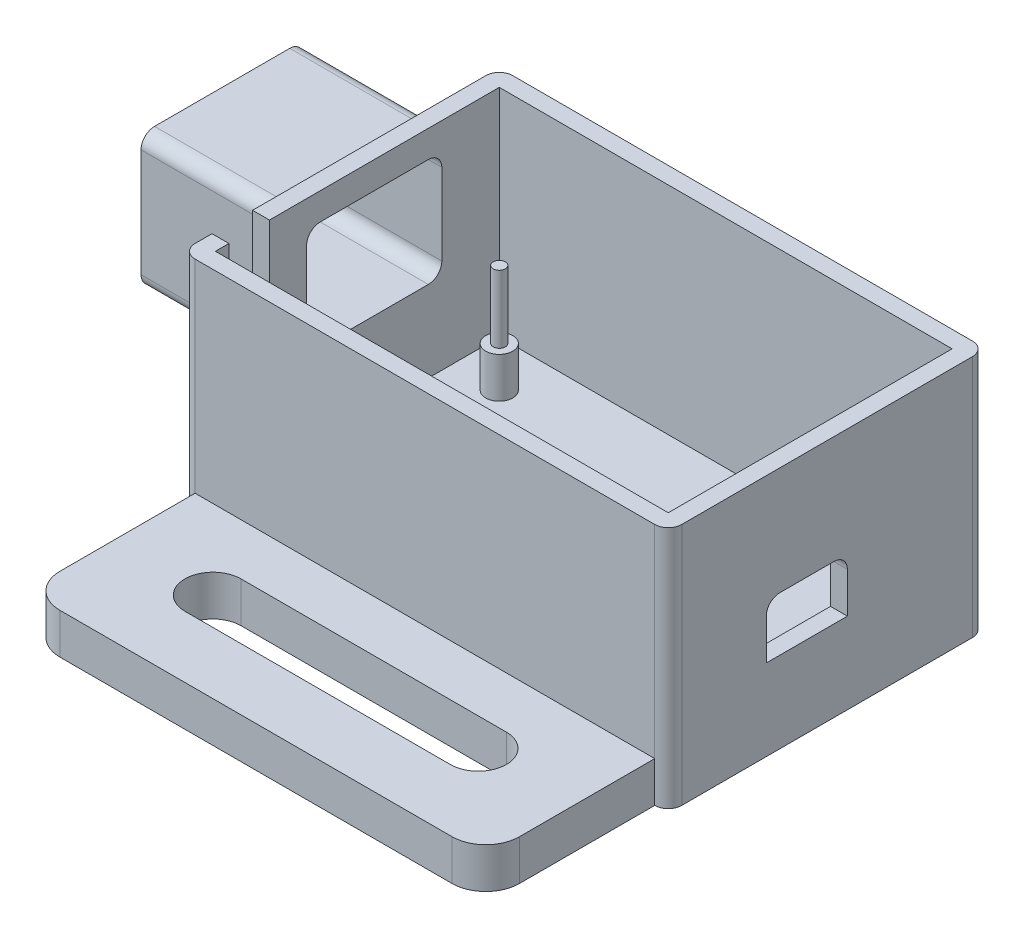
SolidWorks part; units mm, degrees
ref_plane "Front Plane" through (0, 0, 0) normal (0, 0, 1) x (1, 0, 0)
ref_plane "Top Plane" through (0, 0, 0) normal (0, 1, 0) x (1, 0, 0)
ref_plane "Right Plane" through (0, 0, 0) normal (1, 0, 0) x (0, 0, -1)
sketch "Sketch1" plane through (0, 0, 0) normal (0, 1, 0) x (1, 0, 0)
  line L0 (-10.5, -10.5) -> (-10.5, 36.5)
  line L1 (0, 0) -> (51, 0) construction
  line L2 (0, 0) -> (0, 26) construction
  line L3 (0, 26) -> (51, 26) construction
  line L4 (51, 0) -> (51, 26) construction
  line L5 (-10.5, 36.5) -> (61.5, 36.5)
  line L6 (61.5, -10.5) -> (61.5, 36.5)
  line L7 (-10.5, -10.5) -> (61.5, -10.5)
  line L8 (25.5, 36.5) -> (25.5, -10.5) construction
  line L9 (-10.5, 13) -> (61.5, 13) construction
  dimension "D1" = 51
  dimension "D2" = 26
  dimension "D3" = 10.5
extrude "Boss-Extrude1" add sketch "Sketch1" along normal blind 4
sketch "Sketch2" plane through (0, 4, 0) normal (0, 1, 0) x (1, 0, 0)
  line L0 (-3, 13) -> (54, 13) construction
  line L1 (25.5, 29) -> (25.5, -3) construction
  line L8 (-3, 29) -> (-3, -3)
  line L9 (54, 29) -> (-3, 29)
  line L10 (54, -3) -> (54, 29)
  line L11 (-3, -3) -> (54, -3)
  line L12 (-3, 29) -> (-3, -3) construction
  line L13 (54, 29) -> (-3, 29) construction
  line L14 (54, -3) -> (54, 29) construction
  line L15 (-3, -3) -> (54, -3) construction
  circle A4 centre (-1.2, 27.2) radius 0.9
  circle A5 centre (-1.2, -1.2) radius 0.9
  circle A6 centre (52.2, -1.2) radius 0.9
  circle A7 centre (52.2, 27.2) radius 0.9
  dimension "D2" = 1.8
  dimension "D3" = 1.8
  dimension "D4" = 1.8
  dimension "D1" = 7.5
sketch "Sketch3" plane through (0, 4, 0) normal (0, 1, 0) x (1, 0, 0)
  line L0 (61.5, -10.5) -> (61.5, 36.5) construction
  line L1 (-10.5, -10.5) -> (61.5, -10.5) construction
  line L2 (61.5, 36.5) -> (-10.5, 36.5) construction
  line L3 (-10.5, 36.5) -> (-10.5, -10.5) construction
  line L4 (61.5, -10.5) -> (61.5, 36.5)
  line L5 (-10.5, -10.5) -> (61.5, -10.5)
  line L6 (61.5, 36.5) -> (-10.5, 36.5)
  line L7 (-10.5, 36.5) -> (-10.5, -10.5)
  line L8 (59, -8) -> (59, 34)
  line L9 (59, 34) -> (-8, 34)
  line L10 (-8, 34) -> (-8, -8)
  line L11 (-8, -8) -> (59, -8)
  dimension "D1" = 2.5
extrude "Boss-Extrude3" add sketch "Sketch3" along normal blind 32
extrude "Boss-Extrude4" add sketch "Sketch2" along normal blind 16
sketch "Sketch4" plane through (0, 4, 0) normal (0, 1, 0) x (1, 0, 0)
  line L0 (25.5, 34) -> (25.5, -8) construction
  line L1 (59, 34) -> (-8, 34) construction
  line L2 (-8, -8) -> (59, -8) construction
  line L3 (-8, 13) -> (59, 13) construction
  line L4 (-8, 34) -> (-8, -8) construction
  line L5 (59, -8) -> (59, 34) construction
  circle A0 centre (-1.2, 27.2) radius 2
  circle A1 centre (-1.2, -1.2) radius 2
  circle A2 centre (52.2, -1.2) radius 2
  circle A3 centre (52.2, 27.2) radius 2
  dimension "D1" = 4
extrude "Boss-Extrude5" add sketch "Sketch4" along normal blind 6
sketch "Sketch5" plane through (61.5, 0, 0) normal (1, 0, 0) x (0, 0, -1)
  line L1 (-8, 36) -> (-8, 4) construction
  line L7 (4, 20) -> (16, 20)
  line L8 (4, 20) -> (4, 12)
  line L9 (4, 12) -> (16, 12)
  line L10 (16, 20) -> (16, 12)
  line L11 (-8, 4) -> (34, 4) construction
  line L12 (-8, 36) -> (-8, 4) construction
  line L13 (-8, 4) -> (34, 4) construction
  dimension "D1" = 8
  dimension "D2" = 12
  dimension "D3" = 8
  dimension "D4" = 12
extrude "Cut-Extrude1" cut sketch "Sketch5" against normal blind 6
fillet "Fillet2" radius 2 4 edges at (-10.5, 18, 10.5) (-10.5, 18, -36.5) (61.5, 18, -36.5) (61.5, 18, 10.5)
fillet "Fillet3" radius 2 2 edges at (60.25, 20, -4) (60.25, 20, -16)
sketch "Sketch6" plane through (0, 0, 10.5) normal (0, 0, 1) x (1, 0, 0)
  line L0 (-8, 4) -> (59, 4) construction
  line L1 (59, 36) -> (59, 4) construction
  line L2 (-8, 4) -> (59, 4) construction
  line L3 (59, 36) -> (59, 4) construction
  line L5 (28, 24) -> (44, 24)
  line L6 (28, 24) -> (28, 15)
  line L7 (28, 15) -> (44, 15)
  line L8 (44, 24) -> (44, 15)
  dimension "D1" = 16
  dimension "D2" = 9
  dimension "D3" = 15
  dimension "D4" = 11
extrude "Cut-Extrude2" [suppressed] cut sketch "Sketch6" against normal blind 6 contours L7 L8 L5 L6
sketch "Sketch8" [suppressed] plane through (-10.5, 0, 0) normal (-1, 0, 0) x (0, 0, 1)
  line L0 (-34.5, 28) -> (-34.5, 0) construction
  line L1 (-22.5, 20) -> (-10.5, 20)
  line L2 (-22.5, 20) -> (-22.5, 12)
  line L3 (-22.5, 12) -> (-10.5, 12)
  line L4 (-10.5, 20) -> (-10.5, 12)
  line L6 (-34, 4) -> (8, 4) construction
  line L7 (-34, 4) -> (8, 4) construction
  dimension "D1" = 12
  dimension "D2" = 8
  dimension "D3" = 8
  dimension "D4" = 12
sketch "Sketch11" plane through (-10.5, 0, 0) normal (-1, 0, 0) x (0, 0, 1)
  line L0 (-34.5, 36) -> (8.5, 36) construction
  line L1 (-27.5, 34) -> (-3.5, 34)
  line L2 (-27.5, 34) -> (-27.5, 14)
  line L3 (-27.5, 14) -> (-3.5, 14)
  line L4 (-3.5, 34) -> (-3.5, 14)
  line L5 (-34.5, 36) -> (-34.5, 0) construction
  dimension "D1" = 24
  dimension "D2" = 20
  dimension "D3" = 2
  dimension "D4" = 7
extrude "Boss-Extrude7" add sketch "Sketch11" along normal blind 20
sketch "Sketch12" plane through (-8, 0, 0) normal (1, 0, 0) x (0, 0, -1)
  line L0 (27.5, 14) -> (3.5, 14) construction
  line L1 (3.5, 34) -> (27.5, 34) construction
  line L2 (3.5, 14) -> (3.5, 34) construction
  line L3 (27.5, 34) -> (27.5, 14) construction
  line L4 (27.5, 14) -> (3.5, 14) construction
  line L5 (3.5, 34) -> (27.5, 34) construction
  line L6 (3.5, 14) -> (3.5, 34) construction
  line L7 (27.5, 34) -> (27.5, 14) construction
  line L8 (5.5, 16) -> (5.5, 32)
  line L9 (5.5, 32) -> (25.5, 32)
  line L10 (25.5, 32) -> (25.5, 16)
  line L11 (25.5, 16) -> (5.5, 16)
  dimension "D1" = 2
extrude "Cut-Extrude4" cut sketch "Sketch12" against normal blind 20 contours L8 L9 L10 L11
sketch "Sketch13" plane through (-30.5, 0, 0) normal (-1, 0, 0) x (0, 0, 1)
  line L0 (-3.5, 34) -> (-27.5, 34) construction
  line L1 (-23, 28.5) -> (-8, 28.5)
  line L2 (-23, 28.5) -> (-23, 19.5)
  line L3 (-23, 19.5) -> (-8, 19.5)
  line L4 (-8, 28.5) -> (-8, 19.5)
  line L7 (-3.5, 14) -> (-3.5, 34) construction
  dimension "D1" = 15
  dimension "D2" = 9
  dimension "D3" = 5.5
  dimension "D4" = 4.5
extrude "Cut-Extrude5" cut sketch "Sketch13" against normal blind 20
fillet "Fillet4" radius 2 4 edges at (-18, 16, -25.5) (-18, 32, -25.5) (-18, 32, -5.5) (-18, 16, -5.5)
fillet "Fillet5" radius 2 4 edges at (-20.5, 14, -3.5) (-20.5, 34, -3.5) (-20.5, 14, -27.5) (-20.5, 34, -27.5)
sketch "Sketch14" plane through (-10.5, 0, 0) normal (-1, 0, 0) x (0, 0, 1)
  line L0 (-34.5, 0) -> (8.5, 0) construction
  line L1 (0, 37) -> (6, 37)
  line L2 (0, 37) -> (0, 12)
  line L3 (0, 12) -> (6, 12)
  line L4 (6, 37) -> (6, 12)
  dimension "D1" = 6
  dimension "D2" = 25
  dimension "D3" = 12
extrude "Cut-Extrude6" cut sketch "Sketch14" against normal blind 5
fillet "Fillet6" radius 2 2 edges at (-9.25, 12, 6) (-9.25, 12, 0)
sketch "Sketch15" plane through (0, 0, 10.5) normal (0, 0, 1) x (1, 0, 0)
  line L0 (-8.5, 0) -> (59.5, 0) construction
  line L1 (-8.5, 0) -> (59.5, 0)
  line L2 (-8.5, 6) -> (59.5, 6)
  line L3 (-8.5, 6) -> (-8.5, 0)
  line L4 (59.5, 6) -> (59.5, 0)
  dimension "D1" = 6
extrude "Boss-Extrude8" add sketch "Sketch15" along normal blind 25
fillet "Fillet7" radius 5 2 edges at (59.5, 3, 35.5) (-8.5, 3, 35.5)
sketch "Sketch16" plane through (0, 6, 0) normal (0, 1, 0) x (1, 0, 0)
  line L0 (59.5, -10.5) -> (-8.5, -10.5) construction
  line L1 (54.5, -35.5) -> (-3.5, -35.5) construction
  line L2 (59.5, -10.5) -> (-8.5, -10.5) construction
  line L3 (54.5, -35.5) -> (-3.5, -35.5) construction
  line L4 (25.5, -35.5) -> (25.5, -10.5) construction
  line L5 (-8.5, -30.5) -> (-8.5, -10.5) construction
  line L6 (5.87, -22.2289) -> (45.13, -22.2289) construction
  line L7 (5.87, -18.0789) -> (45.13, -18.0789)
  line L8 (5.87, -26.3789) -> (45.13, -26.3789)
  arc A0 (5.87, -18.0789) -> (5.87, -26.3789) centre (5.87, -22.2289) ccw
  arc A1 (45.13, -26.3789) -> (45.13, -18.0789) centre (45.13, -22.2289) ccw
  point P10 (25.5, -22.2289)
  dimension "D1" = 8.3
  dimension "D2" = 34
extrude "Cut-Extrude7" cut sketch "Sketch16" against normal blind 25 contours L8 A1 L7 A0
